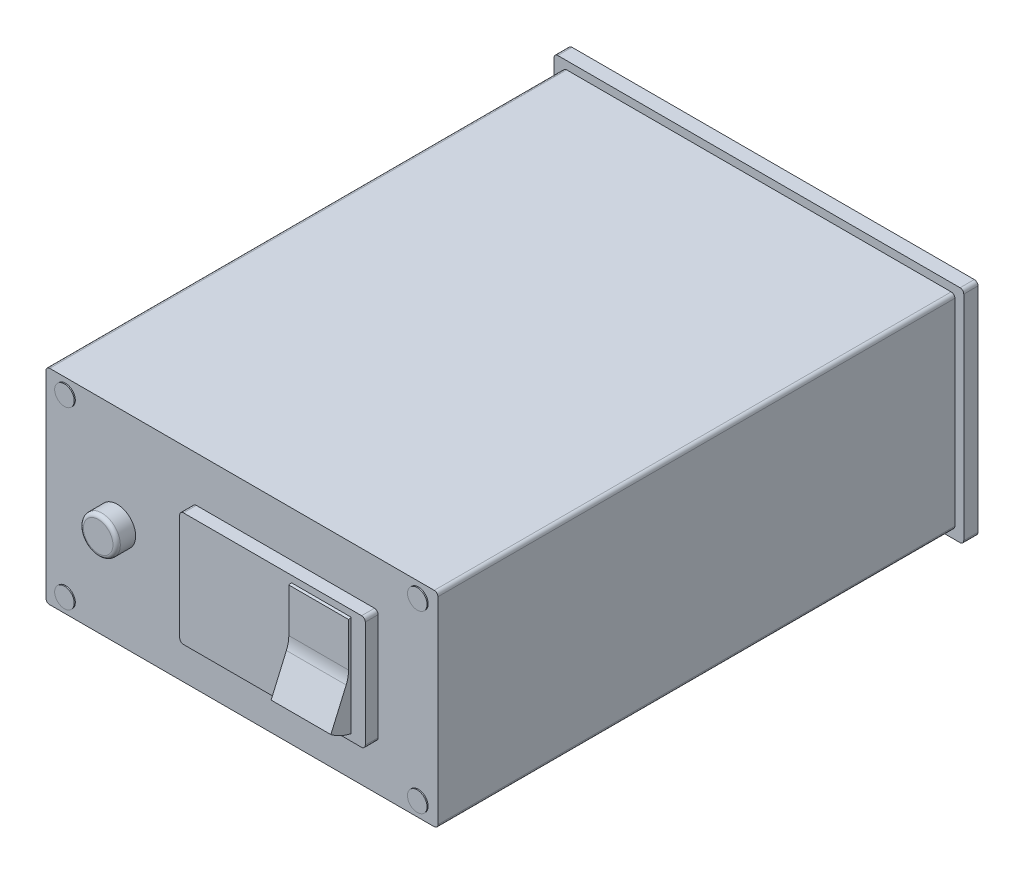
SolidWorks part; units mm, degrees
ref_plane "Front" through (0, 0, 0) normal (0, 0, 1) x (1, 0, 0)
ref_plane "Top" through (0, 0, 0) normal (0, 1, 0) x (1, 0, 0)
ref_plane "Right" through (0, 0, 0) normal (1, 0, 0) x (0, 0, -1)
sketch "Sketch1" plane through (0, 0, 0) normal (0, 0, 1) x (1, 0, 0)
  line L1 (-55.53, -29.925) -> (55.53, -29.925)
  line L2 (-55.53, -29.925) -> (-55.53, 29.925)
  line L3 (-55.53, 29.925) -> (55.53, 29.925)
  line L4 (55.53, -29.925) -> (55.53, 29.925)
  line L5 (-55.53, -29.925) -> (55.53, 29.925) construction
  line L6 (-55.53, 29.925) -> (55.53, -29.925) construction
  point P0 (0, 0)
  dimension "D1" = 59.85
  dimension "D2" = 111.06
extrude "Face" add sketch "Sketch1" along normal blind 3.86
fillet "Face Fillets" radius 1 4 edges at (-55.53, 29.925, 1.93) (-55.53, -29.925, 1.93) (55.53, -29.925, 1.93) (55.53, 29.925, 1.93)
sketch "Sketch2" plane through (0, 0, 0) normal (0, 0, 1) x (1, 0, 0)
  line L1 (-53.125, -27.75) -> (53.125, -27.75)
  line L2 (-53.125, -27.75) -> (-53.125, 27.75)
  line L3 (-53.125, 27.75) -> (53.125, 27.75)
  line L4 (53.125, -27.75) -> (53.125, 27.75)
  line L5 (-53.125, -27.75) -> (53.125, 27.75) construction
  line L6 (-53.125, 27.75) -> (53.125, -27.75) construction
  point P0 (0, 0)
  dimension "D1" = 106.25
  dimension "D2" = 55.5
extrude "Body" add sketch "Sketch2" along normal blind 144
sketch "Sketch3" plane through (0, -27.75, 0) normal (0, -1, 0) x (1, 0, 0)
  line L0 (-54.53, 3.86) -> (54.53, 3.86) construction
  line L1 (-36.625, 18.86) -> (36.625, 18.86) construction
  line L2 (-36.625, 18.86) -> (-36.625, 125.75) construction
  line L3 (-36.625, 125.75) -> (36.625, 125.75) construction
  line L4 (36.625, 18.86) -> (36.625, 125.75) construction
  line L5 (-36.625, 18.86) -> (36.625, 125.75) construction
  line L6 (-36.625, 125.75) -> (36.625, 18.86) construction
  line L7 (-53.125, 144) -> (53.125, 144) construction
  line L9 (-43, 119.375) -> (-30.25, 119.375)
  line L10 (-43, 119.375) -> (-43, 132.125)
  line L11 (-43, 132.125) -> (-30.25, 132.125)
  line L12 (-30.25, 119.375) -> (-30.25, 132.125)
  line L13 (-43, 119.375) -> (-30.25, 132.125) construction
  line L14 (-43, 132.125) -> (-30.25, 119.375) construction
  line L15 (30.25, 119.375) -> (43, 119.375)
  line L16 (30.25, 119.375) -> (30.25, 132.125)
  line L17 (30.25, 132.125) -> (43, 132.125)
  line L18 (43, 119.375) -> (43, 132.125)
  line L19 (30.25, 119.375) -> (43, 132.125) construction
  line L20 (30.25, 132.125) -> (43, 119.375) construction
  line L21 (30.25, 12.485) -> (43, 12.485)
  line L22 (30.25, 12.485) -> (30.25, 25.235)
  line L23 (30.25, 25.235) -> (43, 25.235)
  line L24 (43, 12.485) -> (43, 25.235)
  line L25 (30.25, 12.485) -> (43, 25.235) construction
  line L26 (30.25, 25.235) -> (43, 12.485) construction
  line L27 (-43, 12.485) -> (-30.25, 12.485)
  line L28 (-43, 12.485) -> (-43, 25.235)
  line L29 (-43, 25.235) -> (-30.25, 25.235)
  line L30 (-30.25, 12.485) -> (-30.25, 25.235)
  line L31 (-43, 12.485) -> (-30.25, 25.235) construction
  line L32 (-43, 25.235) -> (-30.25, 12.485) construction
  point P0 (0, 72.305)
  dimension "D1" = 15
  dimension "D2" = 18.25
  dimension "D3" = 73.25
  dimension "D4" = 12.75
extrude "Feet" add sketch "Sketch3" along normal blind 3.33 draft 25
fillet "Body Fillets" radius 1 4 edges at (53.125, 27.75, 73.93) (53.125, -27.75, 73.93) (-53.125, -27.75, 73.93) (-53.125, 27.75, 73.93)
sketch "Sketch4" plane through (0, 0, 144) normal (0, 0, 1) x (1, 0, 0)
  line L0 (-53.125, 26.75) -> (-53.125, -26.75) construction
  circle A0 centre (-33.825, 0) radius 5
  dimension "D1" = 10
  dimension "D2" = 19.3
extrude "GND Bannana Port" add sketch "Sketch4" along normal blind 5.15
fillet "Fillet3" radius 1 1 edges at (-28.825, 0, 149.15)
sketch "Sketch5" plane through (0, 0, 144) normal (0, 0, 1) x (1, 0, 0)
  line L0 (53.125, -26.75) -> (53.125, 26.75) construction
  line L1 (-13.375, -15.45) -> (36.925, -15.45)
  line L2 (-13.375, -15.45) -> (-13.375, 15.45)
  line L3 (-13.375, 15.45) -> (36.925, 15.45)
  line L4 (36.925, -15.45) -> (36.925, 15.45)
  line L5 (-13.375, -15.45) -> (36.925, 15.45) construction
  line L6 (-13.375, 15.45) -> (36.925, -15.45) construction
  point P0 (11.775, 0)
  dimension "D1" = 50.3
  dimension "D2" = 30.9
  dimension "D3" = 16.2
extrude "Power Port" add sketch "Sketch5" along normal blind 3.5
fillet "Fillet4" radius 1 4 edges at (-13.375, 15.45, 145.75) (-13.375, -15.45, 145.75) (36.925, -15.45, 145.75) (36.925, 15.45, 145.75)
ref_plane "Switch Plane" through (25, 0, 0) normal (1, 0, 0) x (0, 0, -1)
sketch "Sketch6" plane through (25, 0, 0) normal (1, 0, 0) x (0, 0, -1)
  line L0 (-148.2, 13.5022) -> (-148.2, 1.6226)
  line L1 (-148.8582, -1.5551) -> (-153, -11.1243)
  line L2 (-144.5, 0) -> (-148.3663, 0) construction
  line L3 (-147.5, -14.45) -> (-147.5, 14.45) construction
  circle A0 centre (-144.5, 0) radius 14 construction
  arc A1 (-148.2, 1.6226) -> (-148.8582, -1.5551) centre (-156.2, 1.6226) cw
  arc A2 (-148.2, 13.5022) -> (-153, -11.1243) centre (-144.5, 0) cw
  point P4 (-148.1629, 13.5475)
  dimension "D1" = 28
  dimension "D2" = 8
  dimension "D3" = 5.5
  dimension "D4" = 0.7
  dimension "D5" = 3
extrude "Boss-Extrude6" add sketch "Sketch6" along normal mid plane 16.2
sketch "Sketch7" plane through (0, 0, 0) normal (0, 0, -1) x (-1, 0, 0)
  line L0 (-55.53, -28.925) -> (-55.53, 28.925) construction
  line L1 (54.53, -29.925) -> (-54.53, -29.925) construction
  circle A0 centre (-34.53, -2.925) radius 6.5
  dimension "D1" = 13
  dimension "D2" = 21
  dimension "D3" = 27
extrude "Boss-Extrude7" add sketch "Sketch7" along normal mid plane 4.7
sketch "Sketch8" plane through (0, 0, 144) normal (0, 0, 1) x (1, 0, 0)
  line L0 (-53.125, 26.75) -> (-53.125, -26.75) construction
  line L1 (52.125, 27.75) -> (-52.125, 27.75) construction
  circle A0 centre (-47.825, 23.75) radius 2.65
  dimension "D1" = 5.3
  dimension "D2" = 5.3
  dimension "D3" = 4
extrude "Boss-Extrude8" add sketch "Sketch8" along normal mid plane 0.6
mirror "Mirror1" about plane through (0, 0, 0) normal (1, 0, 0) of "Boss-Extrude8"
mirror "Mirror2" about plane through (0, 0, 0) normal (0, 1, 0) of "Mirror1", "Boss-Extrude8"
ref_plane "Plane2" through (0, -19, 0) normal (0, 1, 0) x (1, 0, 0)
sketch "Aligner Guide" plane through (0, -19, 0) normal (0, 1, 0) x (1, 0, 0)
  line L0 (-27.6997, 0.4) -> (25.0059, 0.4)
  line L1 (54.53, 0) -> (-54.53, 0) construction
  line L2 (53.525, -10.1769) -> (53.525, -139.7462)
  line L3 (-53.525, -10.1769) -> (-53.525, -139.7462)
  line L4 (-29.1637, -144.4) -> (31.0456, -144.4)
  line L5 (52.125, -144) -> (-52.125, -144) construction
  line L6 (-53.125, -144) -> (-53.125, -3.86) construction
  line L7 (53.125, -3.86) -> (53.125, -144) construction
  dimension "D1" = 0.4
  dimension "D2" = 0.4
  dimension "D3" = 0.4
  dimension "D4" = 0.4
